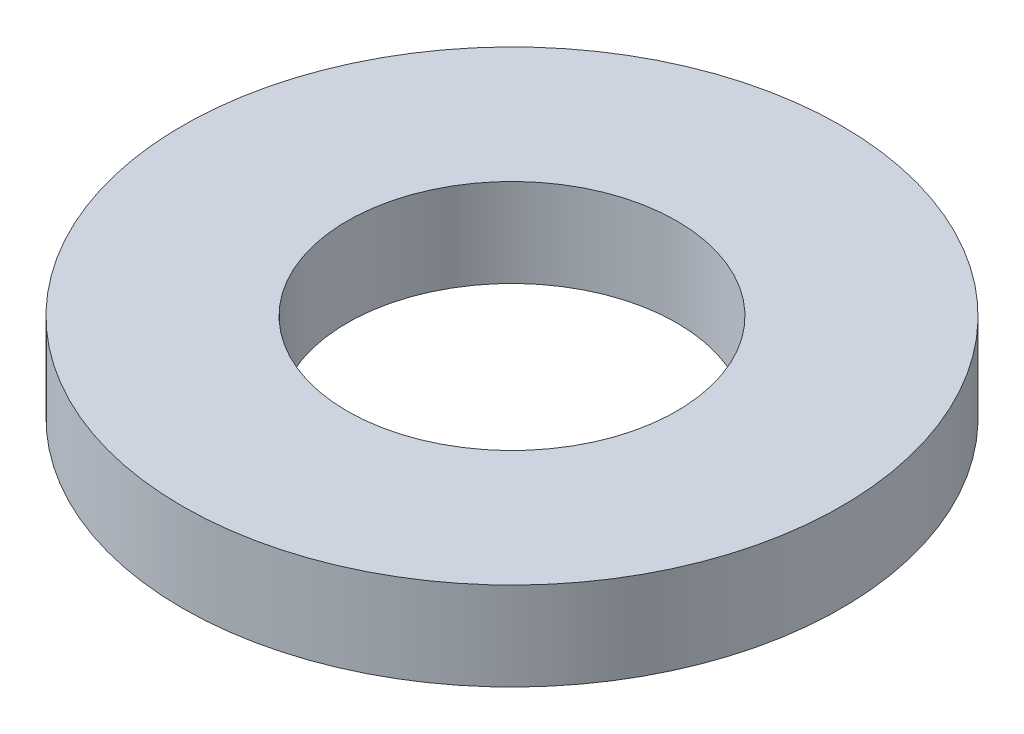
SolidWorks part; units mm, degrees
ref_plane "Front Plane" through (0, 0, 0) normal (0, 0, 1) x (1, 0, 0)
ref_plane "Top Plane" through (0, 0, 0) normal (0, 1, 0) x (1, 0, 0)
ref_plane "Right Plane" through (0, 0, 0) normal (1, 0, 0) x (0, 0, -1)
sketch "Sketch1" plane through (0, 0, 0) normal (0, 1, 0) x (1, 0, 0)
  circle A0 centre (0, 0) radius 6.35
  dimension "OD" = 12.7
extrude "Boss-Extrude1" add sketch "Sketch1" along normal blind 1.7018
sketch "Sketch5" plane through (0, 1.7018, 0) normal (0, 1, 0) x (-1, 0, 0)
  circle A0 centre (0, 0) radius 3.175
  dimension "ID" = 6.35
extrude "Cut-Extrude1" cut sketch "Sketch5" against normal through all
